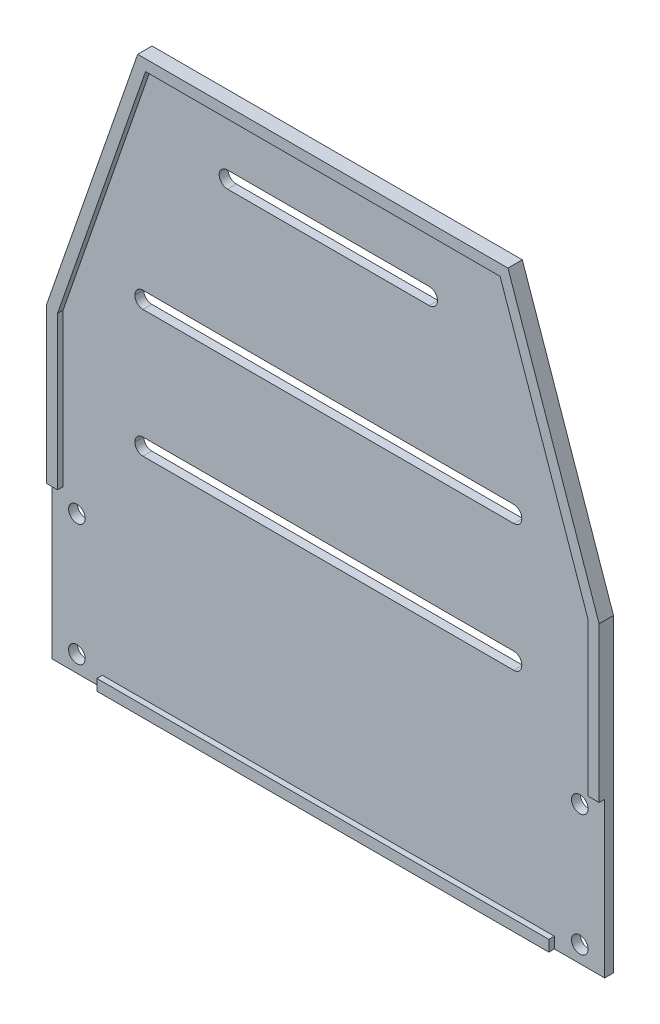
SolidWorks part; units mm, degrees
ref_plane "Front Plane" through (0, 0, 0) normal (0, 0, 1) x (1, 0, 0)
ref_plane "Top Plane" through (0, 0, 0) normal (0, 1, 0) x (1, 0, 0)
ref_plane "Right Plane" through (0, 0, 0) normal (1, 0, 0) x (0, 0, -1)
sketch "Sketch2" plane through (0, 0, 0) normal (0, 0, 1) x (1, 0, 0)
  line L0 (50, 4.25) -> (33.5, 51.75)
  line L1 (-50, -51.75) -> (50, -51.75)
  line L2 (-50, -51.75) -> (-50, 51.75)
  line L3 (-50, 51.75) -> (50, 51.75)
  line L4 (50, -51.75) -> (50, 51.75)
  line L5 (-50, -51.75) -> (50, 51.75) construction
  line L6 (-50, 51.75) -> (50, -51.75) construction
  line L7 (-50, 4.25) -> (-33.5, 51.75)
  point P0 (0, 0)
  dimension "D1" = 100
  dimension "D2" = 103.5
  dimension "D3" = 56
  dimension "D4" = 83.5
  dimension "D5" = 56
  dimension "D6" = 67
extrude "Boss-Extrude1" add sketch "Sketch2" along normal blind 1.6 contours L7 L2 L1 L4 L0 L3
sketch "Sketch4" plane through (0, 0, 1.6) normal (0, 0, 1) x (1, 0, 0)
  line L0 (-50, -51.75) -> (50, -51.75) construction
  line L1 (-50, -51.75) -> (-50, 4.25) construction
  line L2 (0, -0.88) -> (0, 0.88) construction
  circle A0 centre (-45.5, -48.75) radius 1.5
  circle A3 centre (-45.5, -26.75) radius 1.5
  circle A4 centre (45.5, -26.75) radius 1.5
  circle A5 centre (45.5, -48.75) radius 1.5
  dimension "D1" = 3
  dimension "D2" = 3
  dimension "D3" = 4.5
  dimension "D4" = 0
  dimension "D5" = 22
extrude "Cut-Extrude1" cut sketch "Sketch4" against normal blind 1.6
sketch "Sketch5" plane through (0, 0, 1.6) normal (0, 0, 1) x (1, 0, 0)
  line L0 (-33.5, 51.75) -> (33.5, 51.75) construction
  line L1 (0, -0.88) -> (0, 0.88) construction
  circle A0 centre (-18.25, 39.25) radius 1.5
  circle A1 centre (18.25, 39.25) radius 1.5
  dimension "D3" = 3
  dimension "D4" = 36.5
  dimension "D1" = 12.5
  dimension "D2" = 15.25
extrude "Cut-Extrude2" cut sketch "Sketch5" against normal blind 1.6
sketch "Sketch6" plane through (0, 0, 1.6) normal (0, 0, 1) x (1, 0, 0)
  line L0 (-18.25, 40.75) -> (18.25, 40.75)
  line L1 (18.25, 40.75) -> (18.25, 37.75)
  line L2 (18.25, 37.75) -> (-18.25, 37.75)
  line L3 (-18.25, 37.75) -> (-18.25, 40.75)
  circle A0 centre (-18.25, 39.25) radius 1.5 construction
  circle A1 centre (18.25, 39.25) radius 1.5 construction
extrude "Cut-Extrude3" cut sketch "Sketch6" against normal blind 1.6
sketch "Sketch7" plane through (0, 0, 0) normal (0, 0, 1) x (1, 0, 0)
  line L0 (0, -0.88) -> (0, 0.88) construction
  line L1 (-33.55, -11.75) -> (33.55, -11.75)
  line L2 (-35, -10.3) -> (-35, -10.2)
  line L3 (-33.55, -8.75) -> (33.55, -8.75)
  line L4 (35, -10.3) -> (35, -10.2)
  line L5 (-35, -11.75) -> (35, -8.75) construction
  line L6 (-35, -8.75) -> (35, -11.75) construction
  line L7 (-50, -51.75) -> (50, -51.75) construction
  arc A0 (33.55, -11.75) -> (35, -10.3) centre (33.55, -10.3) ccw
  arc A1 (35, -10.2) -> (33.55, -8.75) centre (33.55, -10.2) ccw
  arc A2 (-35, -10.3) -> (-33.55, -11.75) centre (-33.55, -10.3) ccw
  arc A3 (-33.55, -8.75) -> (-35, -10.2) centre (-33.55, -10.2) ccw
  point P0 (0, -10.25)
  dimension "D4" = 1.45
  dimension "D1" = 3
  dimension "D2" = 40
  dimension "D3" = 70
extrude "Cut-Extrude4" cut sketch "Sketch7" along normal up to vertex (1.6 mm away)
sketch "Sketch8" plane through (0, 0, 0) normal (0, 0, 1) x (1, 0, 0)
  line L0 (33.55, -8.75) -> (-33.55, -8.75) construction
  line L1 (-33.55, 11.25) -> (33.55, 11.25)
  line L2 (-35, 12.7) -> (-35, 12.8)
  line L3 (-33.55, 14.25) -> (33.55, 14.25)
  line L4 (35, 12.7) -> (35, 12.8)
  line L5 (-35, 11.25) -> (35, 14.25) construction
  line L6 (-35, 14.25) -> (35, 11.25) construction
  arc A0 (33.55, 11.25) -> (35, 12.7) centre (33.55, 12.7) ccw
  arc A1 (35, 12.8) -> (33.55, 14.25) centre (33.55, 12.8) ccw
  arc A2 (-35, 12.7) -> (-33.55, 11.25) centre (-33.55, 12.7) ccw
  arc A3 (-33.55, 14.25) -> (-35, 12.8) centre (-33.55, 12.8) ccw
  point P0 (0, 12.75)
  dimension "D4" = 1.45
  dimension "D1" = 3
  dimension "D2" = 20
  dimension "D3" = 70
extrude "Cut-Extrude5" cut sketch "Sketch8" along normal blind 1.6
sketch "Sketch9" plane through (0, 0, 0) normal (0, 0, 1) x (1, 0, 0)
  line L0 (50, 4.25) -> (33.5, 51.75)
  line L1 (-50, -51.75) -> (50, -51.75)
  line L2 (-50, -51.75) -> (-50, 51.75)
  line L3 (-50, 51.75) -> (50, 51.75)
  line L4 (50, -51.75) -> (50, 51.75)
  line L5 (-50, -51.75) -> (50, 51.75) construction
  line L6 (-50, 51.75) -> (50, -51.75) construction
  line L7 (-50, 4.25) -> (-33.5, 51.75)
  line L8 (-48.1107, 3.5937) -> (-31.6107, 51.0937)
  line L9 (-48, -49.75) -> (48, -49.75)
  line L10 (48, -49.75) -> (48, 49.75)
  line L11 (-48, 49.75) -> (48, 49.75)
  line L12 (-48, -49.75) -> (-48, 49.75)
  line L13 (48.1107, 3.5937) -> (31.6107, 51.0937)
  line L14 (-50, -51.75) -> (-40.9, -51.75)
  line L15 (-40.9, -51.75) -> (-40.9, -23.75)
  line L16 (-40.9, -23.75) -> (-50, -23.75)
  line L17 (0, -0.88) -> (0, 0.88) construction
  line L18 (40.9, -23.75) -> (50, -23.75)
  line L19 (40.9, -51.75) -> (40.9, -23.75)
  point P0 (0, 0)
  dimension "D1" = 100
  dimension "D2" = 103.5
  dimension "D3" = 56
  dimension "D4" = 83.5
  dimension "D5" = 56
  dimension "D6" = 67
  dimension "D7" = 2
  dimension "D10" = 9.1
  dimension "D11" = 28
  dimension "D8" = 2
  dimension "D9" = 2
extrude "Boss-Extrude3" add sketch "Sketch9" along normal blind 1 from surface at 1.6
